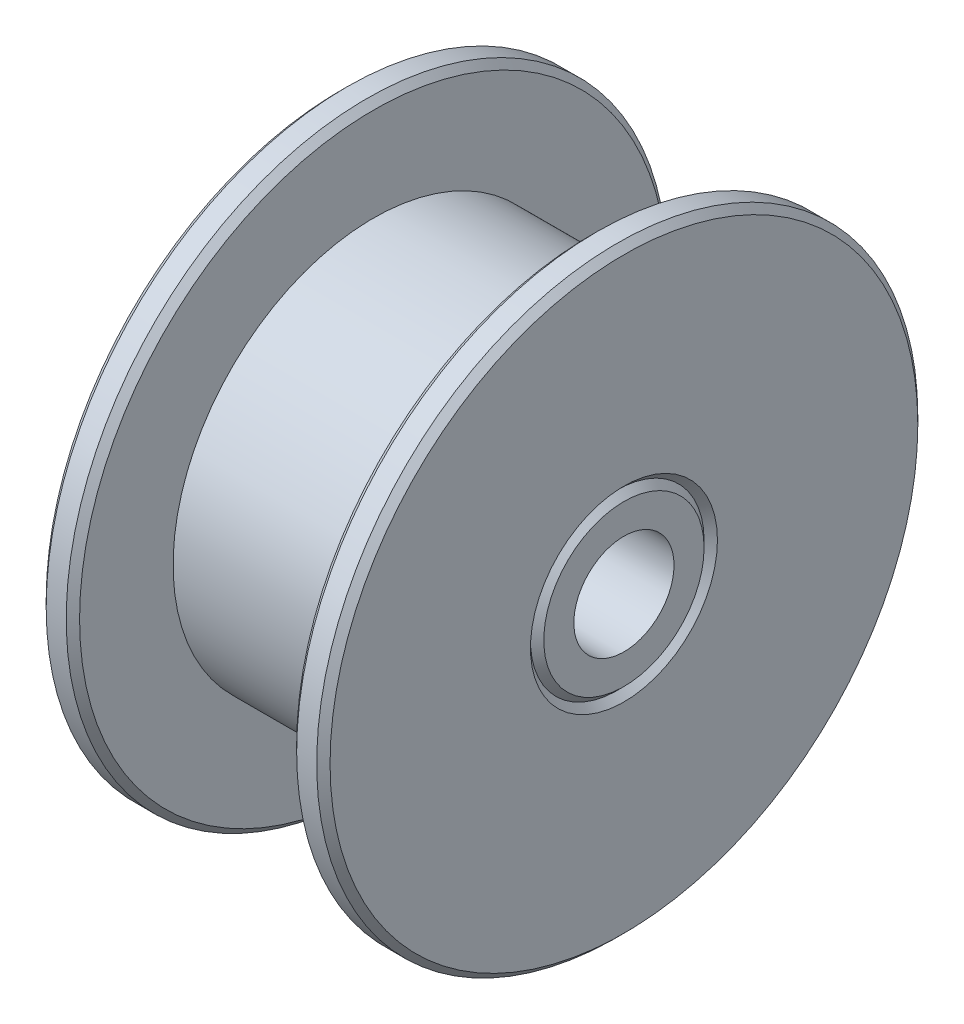
SolidWorks part; units mm, degrees
ref_plane "Front Plane" through (0, 0, 0) normal (0, 0, 1) x (1, 0, 0)
ref_plane "Top Plane" through (0, 0, 0) normal (0, 1, 0) x (1, 0, 0)
ref_plane "Right Plane" through (0, 0, 0) normal (1, 0, 0) x (0, 0, -1)
sketch "Sketch1" plane through (0, 0, 0) normal (0, 0, 1) x (1, 0, 0)
  line L0 (0, 0) -> (0, 9) construction
  line L1 (0, 0) -> (-4.25, 0) construction
  line L2 (-4.25, 1.5) -> (-4.25, 2.4)
  line L3 (0, -0.8938) -> (-3.25, -0.8938) construction
  line L4 (-4.25, 9) -> (-3.25, 9)
  line L5 (0, 6) -> (0, 1.5)
  line L6 (-3.25, 9) -> (-3.25, 6)
  line L7 (-3.25, 6) -> (0, 6)
  line L8 (0, 1.5) -> (-4.25, 1.5)
  line L9 (-4.25, 2.8) -> (-4.25, 9)
  line L10 (-4.25, 2.6) -> (-4.05, 2.6) construction
  line L11 (-4.05, 2.6) -> (-4.25, 2.8)
  line L12 (-4.05, 2.6) -> (-4.25, 2.4)
  dimension "D1" = 1.5
revolve "Revolve1" add sketch "Sketch1" angle 360 about L1
mirror "Mirror1" about plane through (0, 6, 0) normal (1, 0, 0) of bodies 101
chamfer "Chamfer1" distance 0.2 angle 45 4 edges at (3.25, 0, -9) (4.25, 0, -9) (-3.25, 0, -9) (-4.25, 0, -9)
